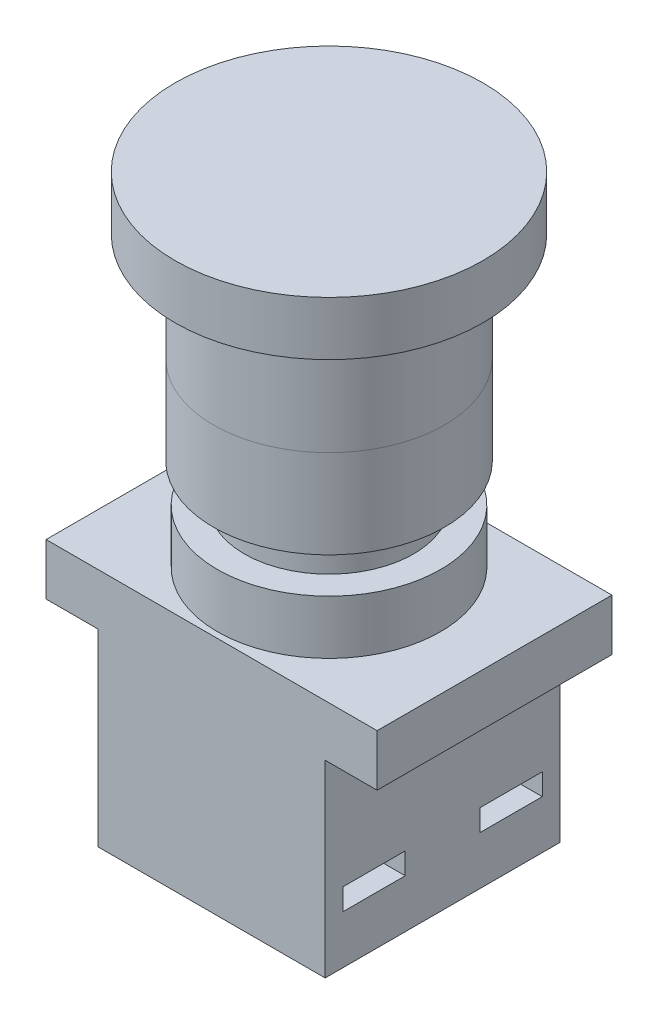
SolidWorks part; units mm, degrees
ref_plane "Plan de face" through (0, 0, 0) normal (0, 0, 1) x (1, 0, 0)
ref_plane "Plan de dessus" through (0, 0, 0) normal (0, 1, 0) x (1, 0, 0)
ref_plane "Plan de droite" through (0, 0, 0) normal (1, 0, 0) x (0, 0, -1)
sketch "Esquisse1" plane through (0, 0, 0) normal (0, 1, 0) x (1, 0, 0)
  circle A0 centre (0, 0) radius 20
  dimension "D1" = 40
extrude "Boss.-Extru.1" add sketch "Esquisse1" against normal blind 7
sketch "Esquisse2" plane through (0, -7, 0) normal (0, -1, 0) x (1, 0, 0)
  circle A0 centre (0, 0) radius 15
  dimension "D1" = 30
extrude "Boss.-Extru.2" add sketch "Esquisse2" along normal blind 14
sketch "Esquisse3" plane through (0, -21, 0) normal (0, -1, 0) x (1, 0, 0)
  circle A1 centre (0, 0) radius 15
  circle A2 centre (0, 0) radius 15
  dimension "D1" = 0
extrude "Boss.-Extru.3" add sketch "Esquisse3" along normal blind 11.5 separate body
sketch "Esquisse4" plane through (0, -32.5, 0) normal (0, -1, 0) x (1, 0, 0)
  circle A0 centre (0, 0) radius 11
  dimension "D1" = 22
extrude "Boss.-Extru.4" add sketch "Esquisse4" along normal blind 12
sketch "Esquisse5" plane through (0, -44.5, 0) normal (0, -1, 0) x (1, 0, 0)
  line L1 (-21.5, 15.25) -> (21.5, 15.25)
  line L2 (-21.5, 15.25) -> (-21.5, -15.25)
  line L3 (-21.5, -15.25) -> (21.5, -15.25)
  line L4 (21.5, 15.25) -> (21.5, -15.25)
  point P4 (-21.5, 0)
  point P6 (0, 15.25)
  dimension "D1" = 43
  dimension "D2" = 30.5
extrude "Boss.-Extru.5" add sketch "Esquisse5" along normal blind 6.7
sketch "Esquisse6" plane through (0, -51.2, 0) normal (0, -1, 0) x (1, 0, 0)
  line L0 (21.5, 15.25) -> (-21.5, 15.25) construction
  line L1 (-14.75, 15.25) -> (14.75, 15.25)
  line L2 (-14.75, 15.25) -> (-14.75, -15.25)
  line L3 (-14.75, -15.25) -> (14.75, -15.25)
  line L4 (14.75, 15.25) -> (14.75, -15.25)
  line L5 (-21.5, -15.25) -> (21.5, -15.25) construction
  point P8 (0, 15.25)
  dimension "D1" = 29.5
extrude "Boss.-Extru.6" add sketch "Esquisse6" along normal blind 24.5
sketch "Esquisse7" plane through (0, -75.7, 0) normal (0, -1, 0) x (1, 0, 0)
  line L0 (0, 0) -> (0, 7.3712) construction
  line L1 (-14.75, 12.95) -> (-4.75, 12.95)
  line L2 (-14.75, 12.95) -> (-14.75, 4.85)
  line L3 (-14.75, 4.85) -> (-4.75, 4.85)
  line L4 (-4.75, 12.95) -> (-4.75, 4.85)
  line L5 (0, 0) -> (3.3307, 0) construction
  line L6 (4.75, 12.95) -> (4.75, 4.85)
  line L7 (14.75, 4.85) -> (4.75, 4.85)
  line L8 (14.75, 12.95) -> (14.75, 4.85)
  line L9 (14.75, 12.95) -> (4.75, 12.95)
  line L10 (14.75, -12.95) -> (4.75, -12.95)
  line L11 (14.75, -12.95) -> (14.75, -4.85)
  line L12 (14.75, -4.85) -> (4.75, -4.85)
  line L13 (4.75, -12.95) -> (4.75, -4.85)
  line L14 (-4.75, -12.95) -> (-4.75, -4.85)
  line L15 (-14.75, -4.85) -> (-4.75, -4.85)
  line L16 (-14.75, -12.95) -> (-14.75, -4.85)
  line L17 (-14.75, -12.95) -> (-4.75, -12.95)
  line L18 (-14.75, 15.25) -> (-14.75, -15.25) construction
  dimension "D1" = 8.1
  dimension "D2" = 9.7
  dimension "D3" = 10
extrude "Enlèv. mat.-Extru.1" cut sketch "Esquisse7" against normal blind 2.8 from offset 6.3 offset against normal yes
sketch "Esquisse8" plane through (0, -44.5, 0) normal (0, 1, 0) x (1, 0, 0)
  circle A0 centre (0, 0) radius 14.5
  dimension "D1" = 29
extrude "bague serrage" add sketch "Esquisse8" along normal blind 7 separate body
